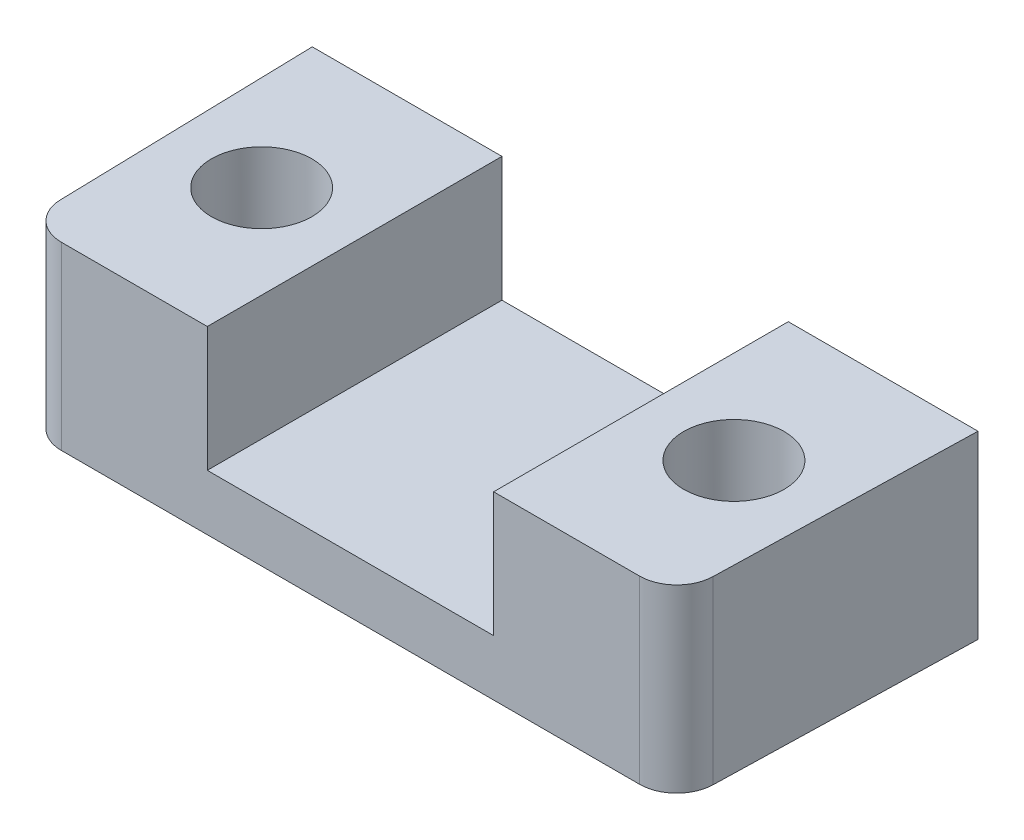
SolidWorks part; units mm, degrees
ref_plane "Front Plane" through (0, 0, 0) normal (0, 0, 1) x (1, 0, 0)
ref_plane "Top Plane" through (0, 0, 0) normal (0, 1, 0) x (1, 0, 0)
ref_plane "Right Plane" through (0, 0, 0) normal (1, 0, 0) x (0, 0, -1)
sketch "Sketch3" plane through (0, 0, 0) normal (0, 1, 0) x (1, 0, 0)
  line L0 (-17.9043, 15.8491) -> (17.9043, 15.8491)
  line L1 (7.7, 15.8491) -> (17.9043, 15.8491) construction
  line L3 (17.5497, 1.949) -> (18.6957, 46.8732)
  line L4 (-18.6957, 46.8732) -> (-17.5497, 1.949)
  line L5 (-15.5504, 0) -> (15.5504, 0)
  line L6 (17.5497, 1.949) -> (17.9043, 15.8491)
  line L7 (-17.9043, 15.8491) -> (-17.5497, 1.949)
  line L8 (-15.5504, 0) -> (15.5504, 0)
  arc A5 (23.5916, 55.2194) -> (18.6957, 46.8732) centre (28.6925, 46.6181) ccw
  arc A6 (23.5916, 55.2194) -> (-23.5916, 55.2194) centre (0, 95) ccw
  arc A7 (-18.6957, 46.8732) -> (-23.5916, 55.2194) centre (-28.6925, 46.6181) ccw
  arc A8 (-17.5497, 1.949) -> (-15.5504, 0) centre (-15.5504, 2) ccw
  arc A9 (15.5504, 0) -> (17.5497, 1.949) centre (15.5504, 2) ccw
  arc A13 (-17.5497, 1.949) -> (-15.5504, 0) centre (-15.5504, 2) ccw
  arc A14 (15.5504, 0) -> (17.5497, 1.949) centre (15.5504, 2) ccw
  dimension "D1" = 0
extrude "Boss-Extrude2" add sketch "Sketch3" along normal offset from surface (9.7 mm away) 2
sketch "Sketch4" plane through (0, 0, 0) normal (0, 0, 1) x (1, 0, 0)
  line L1 (-7.7, 18.4) -> (7.7, 18.4)
  line L2 (-7.7, 18.4) -> (-7.7, 3)
  line L3 (-7.7, 3) -> (7.7, 3)
  line L4 (7.7, 18.4) -> (7.7, 3)
  line L5 (-7.7, 18.4) -> (7.7, 3) construction
  line L6 (-7.7, 3) -> (7.7, 18.4) construction
  circle A0 centre (0, 10.7) radius 8.1 construction
  dimension "D3" = 16.2
  dimension "D1" = 15.4
  dimension "D2" = 10.7
extrude "Cut-Extrude1" cut sketch "Sketch4" against normal through all both and the other way through all
sketch "Sketch5" plane through (0, 9.7, 0) normal (0, 1, 0) x (1, 0, 0)
  circle A0 centre (-12.7011, 7.9245) radius 2.7
  circle A1 centre (12.7011, 7.9245) radius 2.7
  circle A2 centre (-12.7011, 7.9245) radius 2.7 construction
  circle A3 centre (12.7011, 7.9245) radius 2.7 construction
extrude "Cut-Extrude2" cut sketch "Sketch5" against normal through all both and the other way through all
